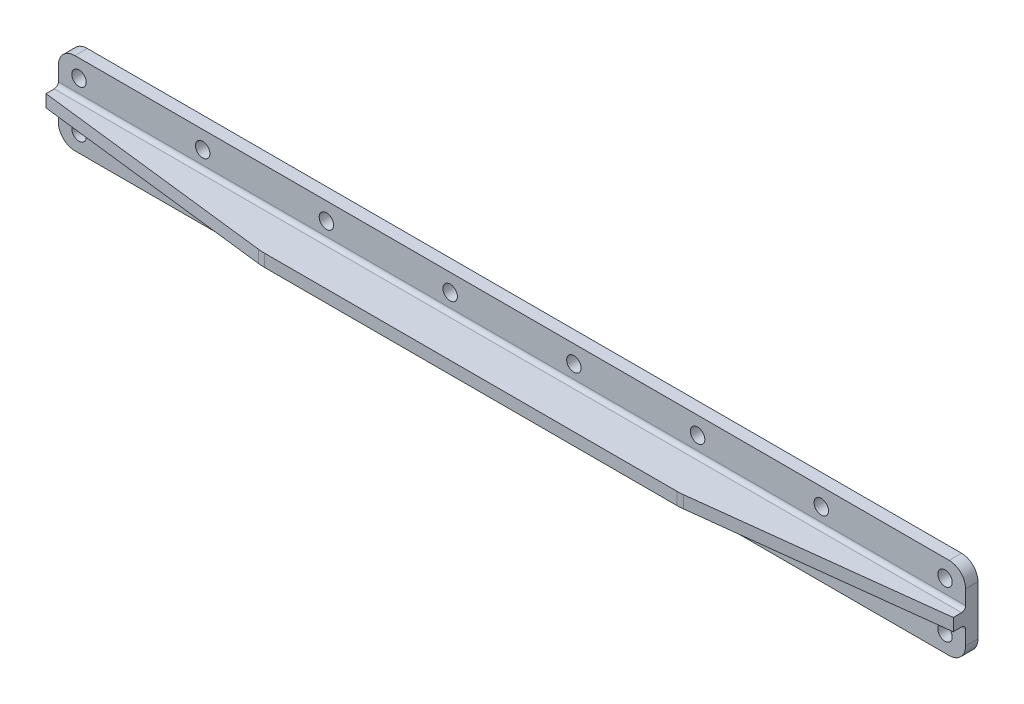
SolidWorks part; units mm, degrees
ref_plane "Top Plane" through (0, 0, 0) normal (0, 0, 1) x (1, 0, 0)
ref_plane "Right Plane" through (0, 0, 0) normal (0, 1, 0) x (1, 0, 0)
ref_plane "Front Plane" through (0, 0, 0) normal (1, 0, 0) x (0, 0, -1)
sketch "Sketch1" plane through (0, 0, 0) normal (1, 0, 0) x (0, 0, -1)
  line L0 (-13, 0) -> (0, 0) construction
  line L1 (-13, -1.5) -> (-13, 1.5)
  line L2 (-13, 1.5) -> (-3, 1.5)
  line L3 (-3, 1.5) -> (-3, 10)
  line L4 (-3, 10) -> (0, 10)
  line L5 (0, 10) -> (0, -10)
  line L6 (-3, -10) -> (0, -10)
  line L7 (-3, -1.5) -> (-3, -10)
  line L8 (-13, -1.5) -> (-3, -1.5)
  dimension "D1" = 3
  dimension "D2" = 3
  dimension "D3" = 20
  dimension "D4" = 10
extrude "Boss-Extrude1" add sketch "Sketch1" along normal mid plane 220
sketch "Sketch2" plane through (0, 0, 3) normal (0, 0, 1) x (1, 0, 0)
  line L0 (0, 18.0483) -> (0, -17.5272) construction
  line L1 (-15, -1.5) -> (-15, -10) construction
  line L4 (110, -10) -> (-110, -10) construction
  line L5 (110, -1.5) -> (-110, -1.5) construction
  line L6 (-45, -5.75) -> (-15, -5.75) construction
  line L7 (45, -5.75) -> (15, -5.75) construction
  line L8 (15, -1.5) -> (15, -10) construction
  line L9 (15, -5.75) -> (-15, -5.75) construction
  line L10 (-102.4934, 0) -> (112.014, 0) construction
  line L11 (15, 5.75) -> (-15, 5.75) construction
  line L12 (15, 1.5) -> (15, 10) construction
  line L13 (45, 5.75) -> (15, 5.75) construction
  line L14 (-45, 5.75) -> (-15, 5.75) construction
  line L15 (-15, 1.5) -> (-15, 10) construction
  circle A0 centre (-15, -5.75) radius 1.75
  circle A1 centre (-15, -5.75) radius 3 construction
  circle A2 centre (-45, -5.75) radius 1.75
  circle A3 centre (-45, -5.75) radius 3 construction
  circle A4 centre (-75, -5.75) radius 1.75
  circle A5 centre (-75, -5.75) radius 3 construction
  circle A6 centre (-105, -5.75) radius 1.75
  circle A7 centre (-105, -5.75) radius 3 construction
  circle A11 centre (105, -5.75) radius 3 construction
  circle A12 centre (75, -5.75) radius 3 construction
  circle A13 centre (45, -5.75) radius 3 construction
  circle A14 centre (15, -5.75) radius 3 construction
  circle A16 centre (105, -5.75) radius 1.75
  circle A17 centre (75, -5.75) radius 1.75
  circle A18 centre (45, -5.75) radius 1.75
  circle A19 centre (15, -5.75) radius 1.75
  circle A20 centre (15, 5.75) radius 3 construction
  circle A21 centre (45, 5.75) radius 3 construction
  circle A22 centre (75, 5.75) radius 3 construction
  circle A23 centre (105, 5.75) radius 3 construction
  circle A26 centre (-105, 5.75) radius 3 construction
  circle A27 centre (-75, 5.75) radius 3 construction
  circle A28 centre (-45, 5.75) radius 3 construction
  circle A29 centre (-15, 5.75) radius 3 construction
  circle A30 centre (15, 5.75) radius 1.75
  circle A31 centre (45, 5.75) radius 1.75
  circle A32 centre (75, 5.75) radius 1.75
  circle A33 centre (105, 5.75) radius 1.75
  circle A36 centre (-105, 5.75) radius 1.75
  circle A37 centre (-75, 5.75) radius 1.75
  circle A38 centre (-45, 5.75) radius 1.75
  circle A39 centre (-15, 5.75) radius 1.75
  dimension "D1" = 6
  dimension "D2" = 3.5
  dimension "D4" = 30
  dimension "D3" = 4
extrude "Cut-Extrude1" cut sketch "Sketch2" against normal through all
sketch "Sketch3" plane through (0, 1.5, 0) normal (0, 1, 0) x (1, 0, 0)
  line L0 (-117.7645, 0) -> (120.942, 0) construction
  line L2 (50, -13) -> (110, -13)
  line L3 (-50, -13) -> (50, -13) construction
  line L4 (51.5257, -12.9102) -> (110, -6)
  line L5 (110, -3) -> (110, -13) construction
  line L6 (-51.5257, -12.9102) -> (-110, -6)
  line L7 (-110, -3) -> (-110, -13) construction
  line L12 (-110, -3) -> (-110, -13)
  line L13 (-110, -13) -> (110, -13)
  line L14 (110, -13) -> (110, -3)
  line L15 (110, -3) -> (-110, -3)
  line L16 (-110, -6) -> (-110, -13)
  line L17 (-110, -13) -> (-50, -13)
  line L18 (110, -13) -> (110, -6)
  arc A1 (50, -13) -> (51.5257, -12.9102) centre (50, 0) ccw
  arc A2 (-51.5257, -12.9102) -> (-50, -13) centre (-50, 0) ccw
  dimension "D2" = 6
  dimension "D1" = 6
  dimension "D6" = 60
  dimension "D7" = 60
  dimension "D4" = 0
extrude "Cut-Extrude2" cut sketch "Sketch3" against normal through all
fillet "Fillet1" radius 4 4 edges at (110, 10, 1.5) (110, -10, 1.5) (-110, -10, 1.5) (-110, 10, 1.5)
fillet "Fillet2" radius 1 2 edges at (0, -1.5, 3) (0, 1.5, 3)
